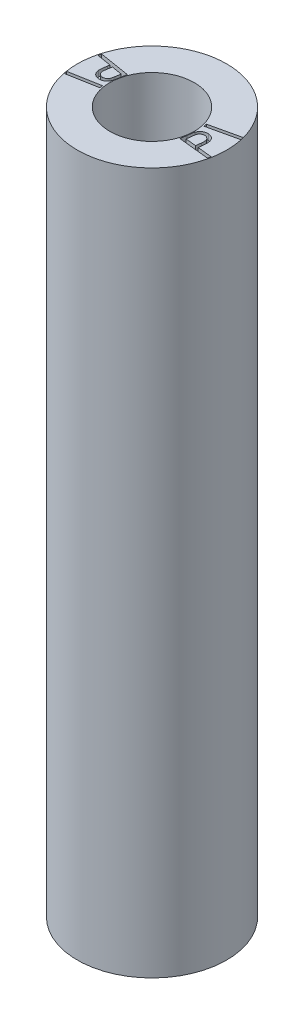
SolidWorks part; units mm, degrees
ref_plane "Front Plane" through (0, 0, 0) normal (0, 0, 1) x (1, 0, 0)
ref_plane "Top Plane" through (0, 0, 0) normal (0, 1, 0) x (1, 0, 0)
ref_plane "Right Plane" through (0, 0, 0) normal (1, 0, 0) x (0, 0, -1)
sketch "Sketch1" plane through (0, 0, 0) normal (0, 1, 0) x (1, 0, 0)
  circle A0 centre (0, 0) radius 2.15
  circle A1 centre (0, 0) radius 3.8
  dimension "D1" = 4.3
  dimension "D2" = 7.6
extrude "Boss-Extrude1" add sketch "Sketch1" along normal blind 35.7
sketch "Sketch2" plane through (0, 35.7, 0) normal (0, 1, 0) x (1, 0, 0)
  text T0 "PI         PI" font "Century Gothic" height in points 6
extrude "Cut-Extrude1" cut sketch "Sketch2" against normal blind 0.3
